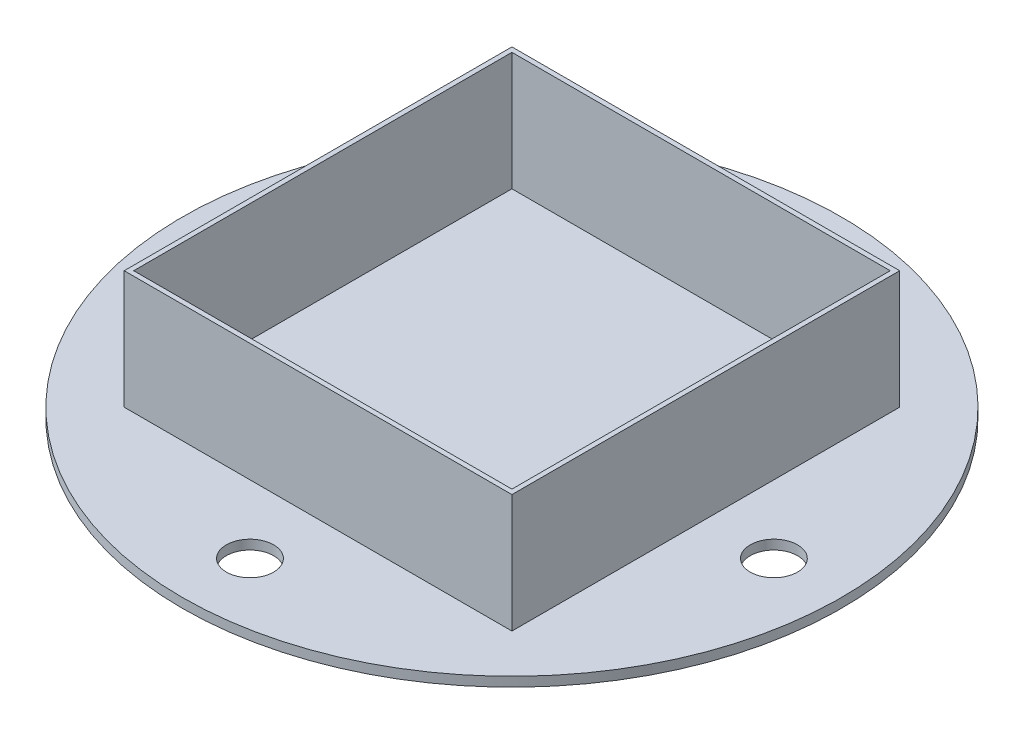
SolidWorks part; units mm, degrees
ref_plane "Front Plane" through (0, 0, 0) normal (0, 0, 1) x (1, 0, 0)
ref_plane "Top Plane" through (0, 0, 0) normal (0, 1, 0) x (1, 0, 0)
ref_plane "Right Plane" through (0, 0, 0) normal (1, 0, 0) x (0, 0, -1)
sketch "Sketch1" plane through (0, 0, 0) normal (0, 1, 0) x (1, 0, 0)
  circle A0 centre (0, 0) radius 88.519
extrude "Boss-Extrude1" add sketch "Sketch1" along normal blind 2.54
sketch "Sketch3" plane through (0, 2.54, 0) normal (0, 1, 0) x (1, 0, 0)
  line L1 (-50.8, 50.8) -> (50.8, 50.8)
  line L2 (-50.8, 50.8) -> (-50.8, -50.8)
  line L3 (-50.8, -50.8) -> (50.8, -50.8)
  line L4 (50.8, 50.8) -> (50.8, -50.8)
  line L7 (-52.07, 52.07) -> (52.07, 52.07)
  line L8 (-52.07, 52.07) -> (-52.07, -52.07)
  line L9 (-52.07, -52.07) -> (52.07, -52.07)
  line L10 (52.07, 52.07) -> (52.07, -52.07)
  point P0 (0, 0)
  point P5 (0, 0)
extrude "Boss-Extrude2" add sketch "Sketch3" along normal blind 31.75 contours L8 L7 L10 L9 | L2 L1 L4 L3
sketch "Sketch4" plane through (0, 2.54, 0) normal (0, 1, 0) x (1, 0, 0)
  line L0 (0, 52.3875) -> (0, 70.4215) construction
  circle A0 centre (0, 70.4215) radius 6.35
  circle A2 centre (0, -70.358) radius 6.35
  circle A3 centre (70.358, 0) radius 6.35
  circle A4 centre (-70.358, 0) radius 6.35
  point P14 (6.7486, -1.0593)
  dimension "D2" = 18.034
extrude "Cut-Extrude1" cut sketch "Sketch4" against normal through all
